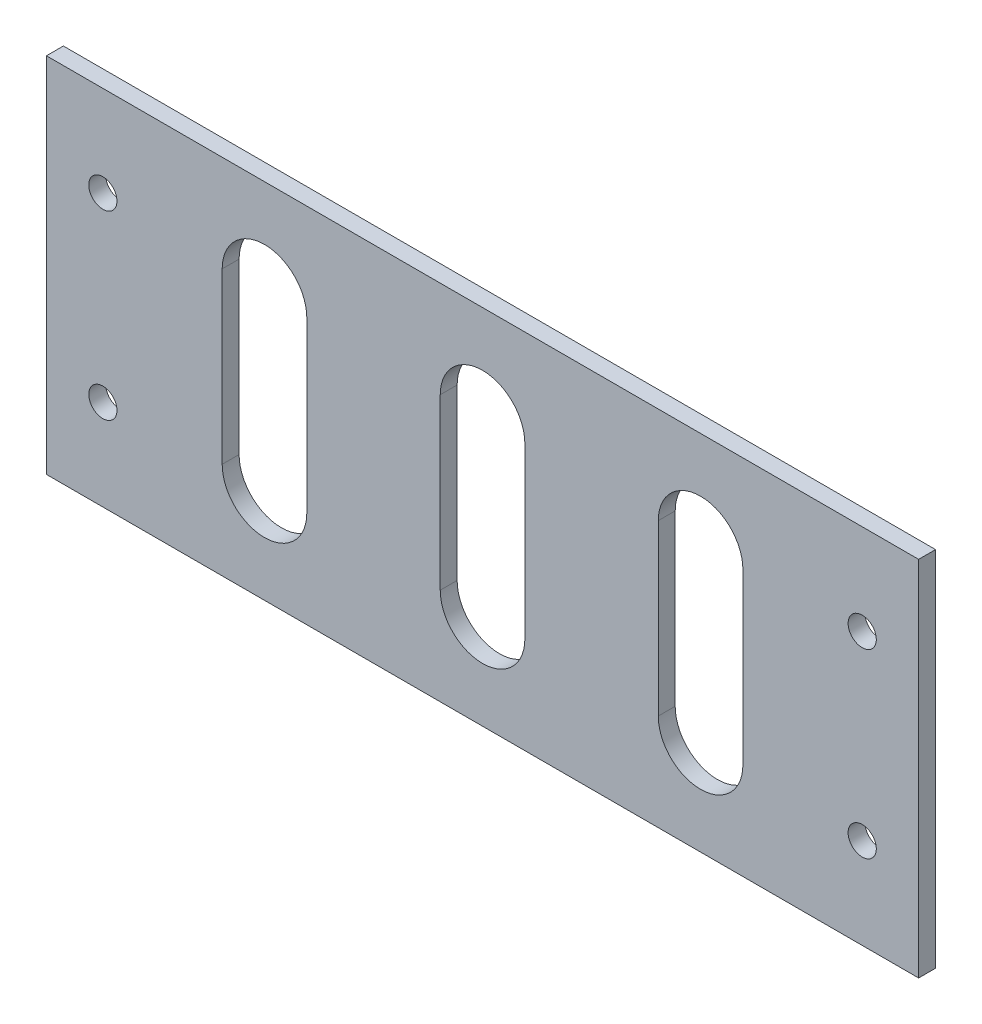
SolidWorks part; units mm, degrees
material "Custom Plastic"
ref_plane "Plan de face" through (0, 0, 0) normal (0, 0, 1) x (1, 0, 0)
ref_plane "Plan de dessus" through (0, 0, 0) normal (0, 1, 0) x (1, 0, 0)
ref_plane "Plan de droite" through (0, 0, 0) normal (1, 0, 0) x (0, 0, -1)
sketch "Esquisse2" plane through (0, 0, 0) normal (0, 1, 0) x (1, 0, 0)
  line L1 (-77.5451, 1.5) -> (77.0549, 1.5)
  line L2 (-77.5451, 1.5) -> (-77.5451, -1.5)
  line L3 (-77.5451, -1.5) -> (77.0549, -1.5)
  line L4 (77.0549, 1.5) -> (77.0549, -1.5)
  line L5 (-77.5451, 1.5) -> (77.0549, -1.5) construction
  line L6 (-77.5451, -1.5) -> (77.0549, 1.5) construction
  line L7 (77.2549, 1.5) -> (77.2549, -1.7) construction
  line L10 (-77.7451, -1.7) -> (-77.7451, 1.5) construction
  point P4 (-0.2451, 0)
  dimension "D1" = 3
  dimension "D2" = 0.2
  dimension "D3" = 0.2
extrude "Boss.-Extru.1" add sketch "Esquisse2" along normal up to surface (64.27 mm away)
sketch "Esquisse3" plane through (0, 0, 1.5) normal (0, 0, 1) x (1, 0, 0)
  line L0 (-54.572, 48.2025) -> (-50054.572, 48.2025) construction
  line L1 (67.0549, 84.4923) -> (67.0549, -49694.1144) construction
  line L4 (-67.5451, 32.135) -> (-77.5451, 32.135) construction
  line L5 (-77.5451, 64.27) -> (-77.5451, 0) construction
  line L7 (-77.5451, 64.27) -> (77.0549, 64.27) construction
  line L8 (77.0549, 32.135) -> (67.0549, 32.135) construction
  line L11 (-77.5451, 0) -> (77.0549, 0) construction
  line L12 (-67.5451, 64.27) -> (-67.5451, 32.135) construction
  line L13 (-67.5451, 32.135) -> (-67.5451, 0) construction
  line L14 (-54.572, 16.0675) -> (-50054.572, 16.0675) construction
  line L16 (77.0549, 64.27) -> (77.0549, 0) construction
  circle A2 centre (-67.5451, 16.0675) radius 2.5
  circle A3 centre (-67.5451, 48.2025) radius 2.5
  circle A4 centre (67.0549, 48.2025) radius 2.5
  circle A5 centre (67.0549, 16.0675) radius 2.5
  point P33 (-67.5451, 48.2025)
  point P35 (-67.5451, 16.0675)
  dimension "D2" = 5
  dimension "D1" = 10
extrude "Enlèv. mat.-Extru.1" cut sketch "Esquisse3" against normal through all
sketch "Esquisse4" plane through (0, 0, 1.5) normal (0, 0, 1) x (1, 0, 0)
  line L0 (-46.3951, 47.135) -> (-46.3951, 17.135)
  line L1 (-31.3951, 17.135) -> (-31.3951, 47.135)
  line L2 (-31.3951, 32.135) -> (-46.3951, 32.135) construction
  line L3 (-46.3951, 17.135) -> (-31.3951, 17.135) construction
  line L4 (-46.3951, 47.135) -> (-31.3951, 47.135) construction
  line L5 (-7.7451, 47.135) -> (-7.7451, 17.135)
  line L6 (7.2549, 17.135) -> (7.2549, 47.135)
  line L7 (7.2549, 32.135) -> (-7.7451, 32.135) construction
  line L8 (-7.7451, 17.135) -> (7.2549, 17.135) construction
  line L9 (-7.7451, 47.135) -> (7.2549, 47.135) construction
  line L10 (30.9049, 47.135) -> (30.9049, 17.135)
  line L11 (45.9049, 17.135) -> (45.9049, 47.135)
  line L12 (45.9049, 32.135) -> (30.9049, 32.135) construction
  line L13 (30.9049, 17.135) -> (45.9049, 17.135) construction
  line L14 (30.9049, 47.135) -> (45.9049, 47.135) construction
  line L15 (-77.5451, 64.27) -> (-77.5451, 74.27) construction
  line L16 (-77.5451, 74.27) -> (-38.8951, 74.27) construction
  line L17 (-38.8951, 74.27) -> (-0.2451, 74.27) construction
  line L18 (-0.2451, 74.27) -> (38.4049, 74.27) construction
  line L19 (38.4049, 74.27) -> (77.0549, 74.27) construction
  line L20 (77.0549, 74.27) -> (77.0549, 64.27) construction
  line L21 (-38.8951, 74.27) -> (-38.8951, -49925.73) construction
  line L22 (-0.2451, 75.8687) -> (-0.2451, -49924.1313) construction
  line L23 (38.4049, 74.27) -> (38.4049, -49925.73) construction
  line L24 (77.0549, 32.135) -> (83.5571, 32.135) construction
  line L26 (77.0549, 64.27) -> (77.0549, 0) construction
  arc A0 (-31.3951, 47.135) -> (-46.3951, 47.135) centre (-38.8951, 47.135) ccw
  arc A1 (-31.3951, 17.135) -> (-46.3951, 17.135) centre (-38.8951, 17.135) cw
  arc A2 (7.2549, 47.135) -> (-7.7451, 47.135) centre (-0.2451, 47.135) ccw
  arc A3 (7.2549, 17.135) -> (-7.7451, 17.135) centre (-0.2451, 17.135) cw
  arc A4 (45.9049, 47.135) -> (30.9049, 47.135) centre (38.4049, 47.135) ccw
  arc A5 (45.9049, 17.135) -> (30.9049, 17.135) centre (38.4049, 17.135) cw
  point P8 (-38.8951, 32.135)
  point P39 (-0.2451, 32.135)
  point P40 (38.4049, 32.135)
  point P44 (77.0549, 32.135)
  dimension "D2" = 15
  dimension "D1" = 15
  dimension "D3" = 15
  dimension "D4" = 10
  dimension "D5" = 30
extrude "Enlèv. mat.-Extru.2" cut sketch "Esquisse4" against normal through all
